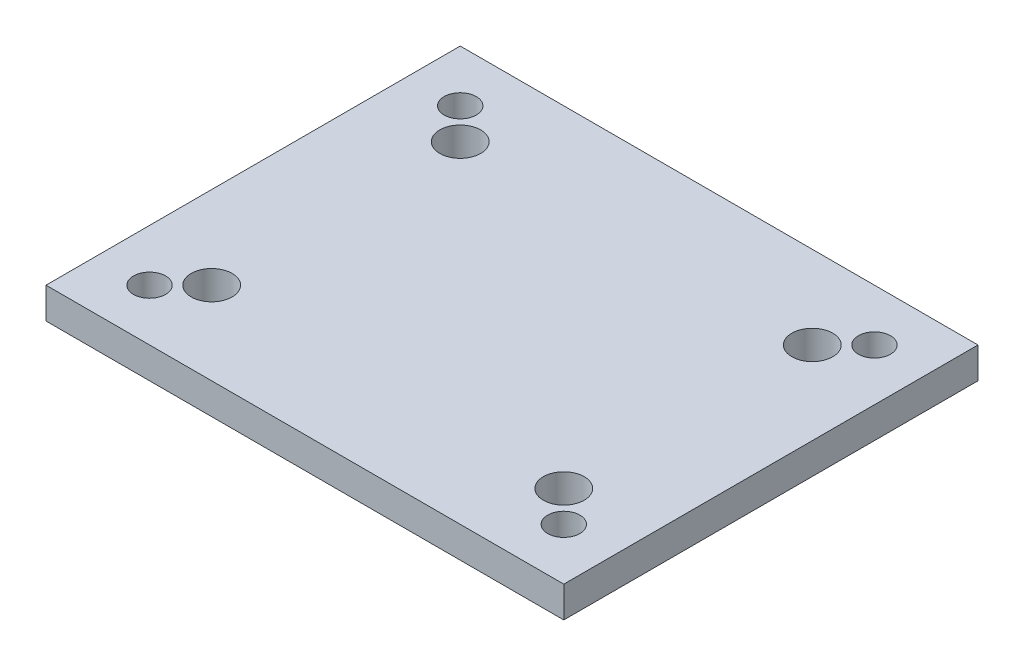
SolidWorks part; units mm, degrees
ref_plane "Front Plane" through (0, 0, 0) normal (0, 0, 1) x (1, 0, 0)
ref_plane "Top Plane" through (0, 0, 0) normal (0, 1, 0) x (1, 0, 0)
ref_plane "Right Plane" through (0, 0, 0) normal (1, 0, 0) x (0, 0, -1)
sketch "Sketch1" plane through (0, 0, 0) normal (0, 1, 0) x (1, 0, 0)
  line L0 (25, 40) -> (25, 0) construction
  line L1 (0, 0) -> (50, 0)
  line L2 (0, 0) -> (0, 40)
  line L3 (0, 40) -> (50, 40)
  line L4 (50, 0) -> (50, 40)
  line L5 (0, 20) -> (50, 20) construction
  circle A0 centre (5, 35) radius 1.55
  circle A1 centre (45, 35) radius 1.55
  circle A2 centre (5, 5) radius 1.55
  circle A3 centre (45, 5) radius 1.55
  circle A4 centre (8, 32) radius 1.975
  circle A5 centre (42, 32) radius 1.975
  circle A6 centre (8, 8) radius 1.975
  circle A7 centre (42, 8) radius 1.975
  point P25 (0, 0)
  point P26 (0, 0)
  point P27 (0, 0)
  point P28 (0, 0)
  dimension "D3" = 3.1
  dimension "D10" = 3.95
  dimension "D1" = 50
  dimension "D2" = 40
  dimension "D4" = 20
  dimension "D5" = 20
  dimension "D6" = 20
  dimension "D7" = 20
  dimension "D8" = 15
  dimension "D9" = 15
  dimension "D11" = 17
  dimension "D12" = 17
  dimension "D13" = 12
  dimension "D14" = 12
extrude "Boss-Extrude1" add sketch "Sketch1" along normal blind 3
equation "\"D5@Sketch1\"=\"D4@Sketch1\""
equation "\"D7@Sketch1\"=\"D6@Sketch1\""
equation "\"D12@Sketch1\"=\"D11@Sketch1\""
equation "\"D14@Sketch1\"=\"D13@Sketch1\""
